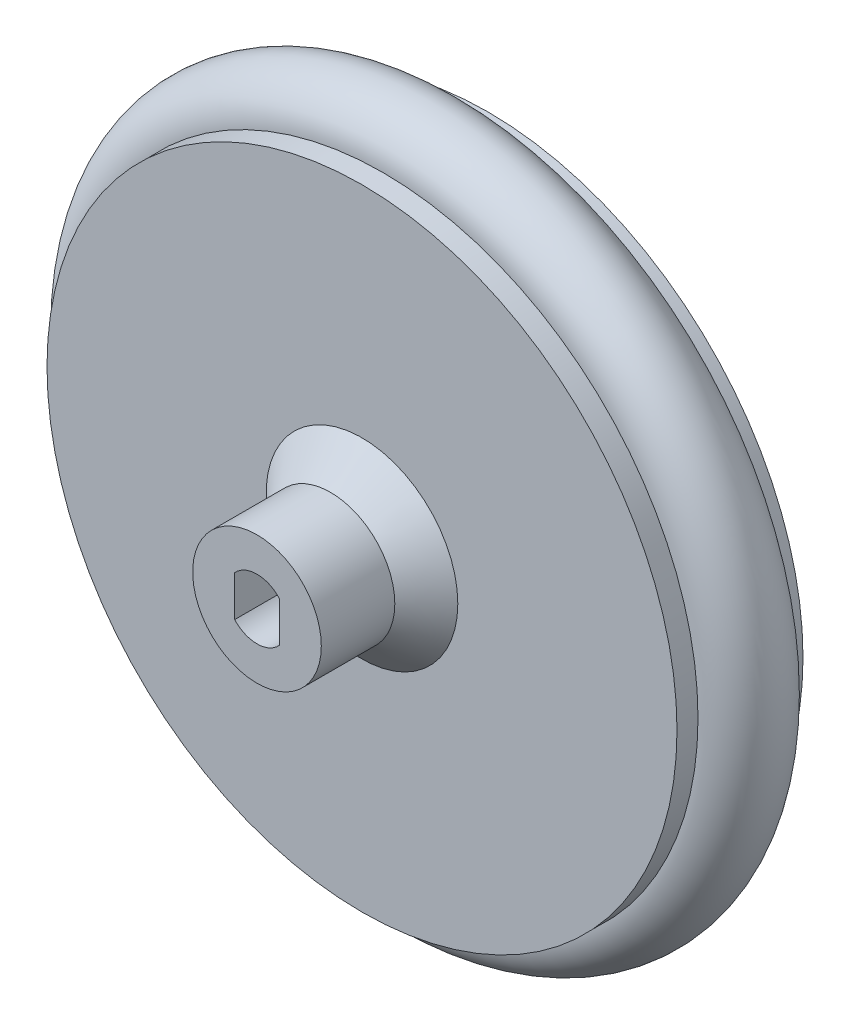
SolidWorks part; units mm, degrees
ref_plane "Alzado" through (0, 0, 0) normal (0, 0, 1) x (1, 0, 0)
ref_plane "Planta" through (0, 0, 0) normal (0, 1, 0) x (1, 0, 0)
ref_plane "Vista lateral" through (0, 0, 0) normal (1, 0, 0) x (0, 0, -1)
sketch "Croquis1" plane through (0, 0, 0) normal (0, 0, 1) x (1, 0, 0)
  circle A0 centre (0, 0) radius 30
  dimension "D1" = 60
extrude "Saliente-Extruir1" add sketch "Croquis1" along normal blind 12
sketch "Croquis2" plane through (0, 0, 0) normal (0, 1, 0) x (1, 0, 0)
  line L0 (-30, 0) -> (-30, -12) construction
  line L1 (0, 0) -> (0, -14.4891) construction
  circle A0 centre (-30, -6) radius 4
  dimension "D1" = 8
revolve "Cortar-Revolución1" cut sketch "Croquis2" angle 360 about L1
sketch "Croquis3" plane through (0, 0, 12) normal (0, 0, 1) x (1, 0, 0)
  line L0 (-2.125, 1.9365) -> (-2.125, -1.9365)
  line L1 (0, 0) -> (0, -6.0283) construction
  line L2 (2.125, 1.9365) -> (2.125, -1.9365)
  circle A0 centre (0, 0) radius 6.125
  arc A1 (-2.125, -1.9365) -> (2.125, -1.9365) centre (0, 0) ccw
  arc A2 (2.125, 1.9365) -> (-2.125, 1.9365) centre (0, 0) ccw
  dimension "D2" = 5.75
  dimension "D3" = 3.25
  dimension "D1" = 2.125
extrude "Saliente-Extruir2" add sketch "Croquis3" along normal blind 10
sketch "Croquis4" plane through (0, 0, 12) normal (0, 0, 1) x (1, 0, 0)
  circle A0 centre (0, 0) radius 1.25
  dimension "D1" = 2.5
extrude "Cortar-Extruir1" cut sketch "Croquis4" against normal through all
chamfer "Chaflán1" distance 3 angle 45 1 edges at (6.125, 0, 12)
sketch "Croquis5" plane through (0, 0, 0) normal (1, 0, 0) x (0, 0, -1)
  line L0 (0, 0) -> (23.1659, 0) construction
  line L1 (-6, 26) -> (-6, 30.5942) construction
  circle A0 centre (-6, 30) radius 4
  arc A1 (-10, 30) -> (-2, 30) centre (-6, 30) ccw construction
revolve "Revolución1" add sketch "Croquis5" angle 360 about L0
